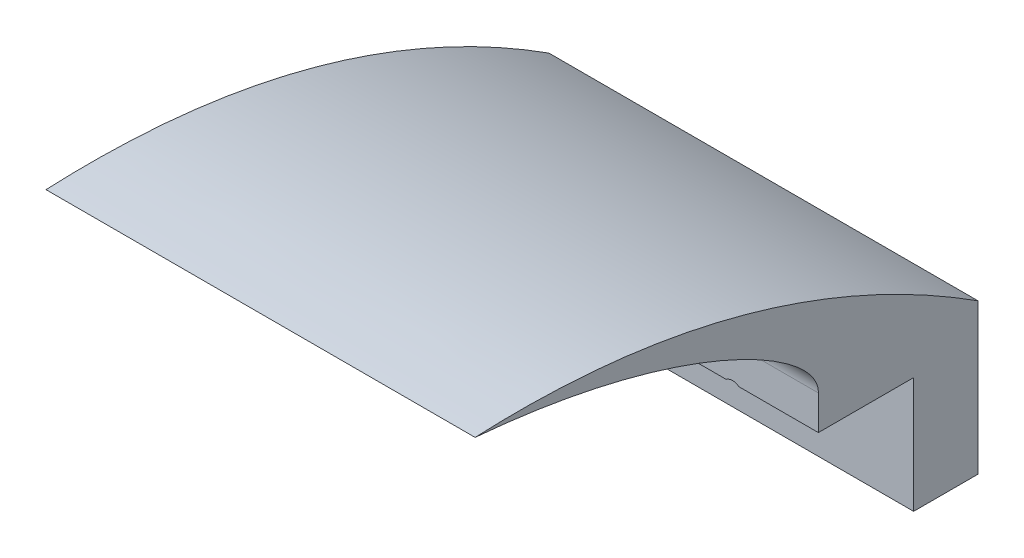
SolidWorks part; units mm, degrees
material "Thornel Mat VMA Foam Core"
ref_plane "Front Plane" through (0, 0, 0) normal (0, 0, 1) x (1, 0, 0)
ref_plane "Top Plane" through (0, 0, 0) normal (0, 1, 0) x (1, 0, 0)
ref_plane "Right Plane" through (0, 0, 0) normal (1, 0, 0) x (0, 0, -1)
curve "Curve1"
  spline degree 3 poles (0, 0.0012, 1.0003) (0, 0.0015, 0.9994) (0, 0.0028, 0.9958) (0, 0.0055, 0.9879) (0, 0.0099, 0.9747) (0, 0.0159, 0.9565) (0, 0.0233, 0.9333) (0, 0.0318, 0.9054) (0, 0.0411, 0.8731) (0, 0.051, 0.8366) (0, 0.0612, 0.7964) (0, 0.0713, 0.7528) (0, 0.0811, 0.7063) (0, 0.0903, 0.6574) (0, 0.0985, 0.6067) (0, 0.1057, 0.5546) (0, 0.1115, 0.5018) (0, 0.1158, 0.4488) (0, 0.1186, 0.3959) (0, 0.1189, 0.3436) (0, 0.1164, 0.2927) (0, 0.1112, 0.2442) (0, 0.1037, 0.1988) (0, 0.0942, 0.157) (0, 0.0831, 0.1194) (0, 0.0711, 0.0865) (0, 0.0584, 0.0585) (0, 0.0457, 0.0357) (0, 0.0334, 0.0184) (0, 0.0218, 0.0064) (0, 0.0108, -0.0005) (0, -0.0003, -0.0011) (0, -0.0092, 0.0055) (0, -0.0148, 0.017) (0, -0.0185, 0.0329) (0, -0.0204, 0.0533) (0, -0.0208, 0.0781) (0, -0.0198, 0.107) (0, -0.0176, 0.1398) (0, -0.0147, 0.176) (0, -0.0111, 0.2153) (0, -0.0074, 0.2574) (0, -0.0037, 0.3019) (0, -0.0005, 0.3484) (0, 0.002, 0.397) (0, 0.0037, 0.4471) (0, 0.0055, 0.4983) (0, 0.0069, 0.5496) (0, 0.0079, 0.6006) (0, 0.0085, 0.6505) (0, 0.0086, 0.699) (0, 0.0083, 0.7455) (0, 0.0076, 0.7894) (0, 0.0065, 0.8302) (0, 0.0053, 0.8675) (0, 0.0039, 0.9007) (0, 0.0027, 0.9296) (0, 0.0013, 0.9539) (0, 0.0006, 0.9727) (0, -0.0011, 0.9872) (0, 0, 0.9944) (0, -0.002, 0.9999) (0, -0.0005, 1) (0, 0, 1) knots 0 0 0 0 0.001372 0.005465 0.012235 0.021602 0.033461 0.047671 0.064081 0.082496 0.102719 0.124527 0.147676 0.171913 0.196978 0.222597 0.248497 0.274385 0.300041 0.32569 0.350525 0.37428 0.396711 0.417577 0.436654 0.453744 0.46868 0.481329 0.491631 0.499616 0.505546 0.510185 0.514824 0.520702 0.528516 0.538466 0.550543 0.564643 0.580638 0.598345 0.617584 0.638174 0.659922 0.682632 0.706121 0.730727 0.7557 0.780732 0.805564 0.829932 0.85357 0.876213 0.89761 0.917519 0.935698 0.951943 0.966047 0.97784 0.987174 0.993932 0.998018 0.999386 1 1 1 1
sketch "Sketch1" plane through (0, 0, 0) normal (1, 0, 0) x (0, 0, -1)
  line L1 (0.8093, 1.5275) -> (0.8093, -8.6325)
  line L3 (48.0533, 1.5275) -> (48.0533, -42.9225)
  line L4 (48.0533, -42.9225) -> (29.0033, -42.9225)
  line L5 (29.0033, -42.9225) -> (29.0033, -8.6325)
  line L6 (29.0033, -8.6325) -> (0.8093, -8.6325)
  line L8 (0.5507, 0) -> (-0.5507, 0) construction
  line L10 (0, 0.0768) -> (0, -0.0768) construction
  spline S0 degree 2 poles (-100.7907, 40.9362) (-19.4323, 44.7232) (48.0533, 1.5275) knots 0 0 0 1 1 1
  spline S1 degree 3 poles (-100.7907, 40.9362) (-95.812, 40.5065) (-85.4041, 39.3561) (-70.047, 36.8254) (-55.2045, 33.4552) (-41.8487, 29.54) (-30.1359, 25.2555) (-20.1921, 20.775) (-12.1117, 16.2715) (-5.9305, 11.9042) (-1.6817, 7.7681) (0.4919, 4.2872) (0.8118, 2.163) (0.8093, 1.5275) knots 0.353791 0.353791 0.353791 0.353791 0.37428 0.396711 0.417577 0.436654 0.453744 0.46868 0.481329 0.491631 0.499616 0.505546 0.508115 0.508115 0.508115 0.508115
  point P2 (0, 0)
  point P3 (-100.7907, 40.9362)
  point P9 (0, 0)
  point P10 (0, 0)
  point P15 (-395.8823, 0.0236)
  dimension "D2" = 1.5275
  dimension "D3" = 10.16
  dimension "D5" = 100.7907
  dimension "D6" = 47.244
  dimension "D7" = 44.45
  dimension "D8" = 34.29
  dimension "D9" = 19.05
  dimension "D10" = 29.1024
  dimension "D11" = 9.7768
  dimension "D12" = 48.0533
  dimension "D14" = 40.9362
extrude "Boss-Extrude1" add sketch "Sketch1" along normal mid plane 127
sketch "Sketch2" plane through (0, 0, -48.0533) normal (0, 0, -1) x (-1, 0, 0)
  line L0 (-63.5, -11.1725) -> (-38.1, -11.1725) construction
  line L1 (-63.5, -42.9225) -> (-63.5, 1.5275) construction
  line L2 (-38.1, -11.1725) -> (38.1, -11.1725) construction
  line L3 (38.1, -11.1725) -> (63.5, -11.1725) construction
  line L4 (63.5, -42.9225) -> (63.5, 1.5275) construction
  line L5 (-63.5, 1.5275) -> (63.5, 1.5275) construction
  circle A0 centre (-38.1, -11.1725) radius 3.175
  circle A1 centre (38.1, -11.1725) radius 3.175
  point P8 (0, 0)
  point P11 (0, 0)
  dimension "D1" = 6.35
  dimension "D2" = 25.4
  dimension "D3" = 12.7
extrude "Cut-Extrude1" cut sketch "Sketch2" against normal through all both and the other way through all
